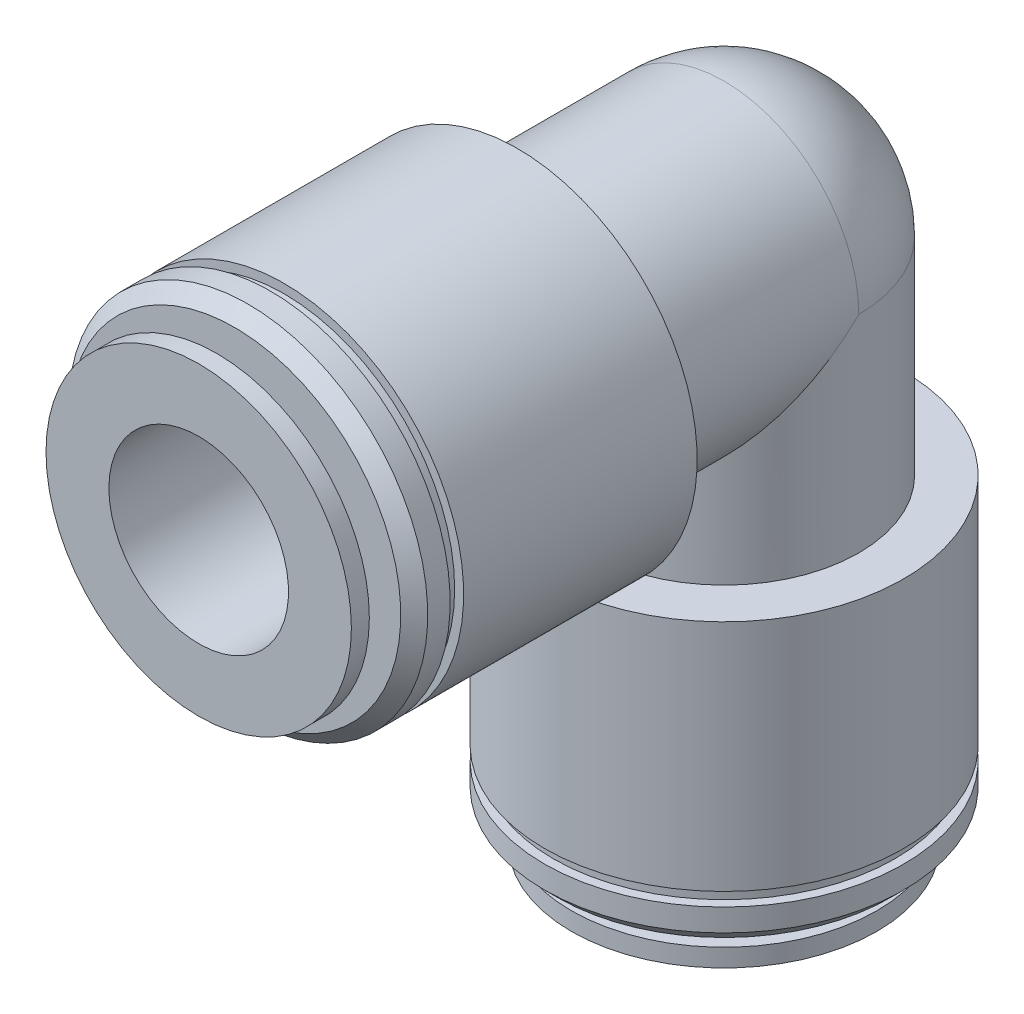
SolidWorks part; units mm, degrees
ref_plane "Спереди" through (0, 0, 0) normal (0, 0, 1) x (1, 0, 0)
ref_plane "Сверху" through (0, 0, 0) normal (0, 1, 0) x (1, 0, 0)
ref_plane "Справа" through (0, 0, 0) normal (1, 0, 0) x (0, 0, -1)
sketch "Эскиз2" plane through (0, 0, 0) normal (0, 0, 1) x (1, 0, 0)
  line L0 (0, 22.5) -> (0, 37.5)
  line L2 (0, 22.5) -> (7.5, 22.5)
  line L3 (7.5, 22.5) -> (7.5, 30)
  arc A0 (7.5, 30) -> (0, 37.5) centre (0, 30) ccw
revolve "Повернуть1" add sketch "Эскиз2" angle 360 about L0
sketch "Эскиз3" plane through (0, 0, 0) normal (0, 0, 1) x (1, 0, 0)
  arc A0 (7.5, 30) -> (-7.5, 30) centre (0, 30) ccw construction
  circle A1 centre (0, 30) radius 7.5
  dimension "D1" = 15
extrude "Бобышка-Вытянуть2" add sketch "Эскиз3" along normal blind 11.5
sketch "Эскиз4" plane through (0, 0, 11.5) normal (0, 0, 1) x (1, 0, 0)
  circle A0 centre (0, 30) radius 10
  dimension "D1" = 20
extrude "Бобышка-Вытянуть3" add sketch "Эскиз4" along normal blind 13
sketch "Эскиз7" plane through (0, 22.5, 0) normal (0, -1, 0) x (1, 0, 0)
  circle A1 centre (0, 0) radius 7.5
  dimension "D1" = 15
extrude "Бобышка-Вытянуть4" add sketch "Эскиз7" along normal blind 4
sketch "Эскиз8" plane through (0, 18.5, 0) normal (0, -1, 0) x (1, 0, 0)
  circle A0 centre (0, 0) radius 10
  dimension "D1" = 20
extrude "Бобышка-Вытянуть6" add sketch "Эскиз8" along normal blind 13 contours A0
sketch "Эскиз9" plane through (0, 0, 0) normal (1, 0, 0) x (0, 0, -1)
  line L15 (8.5, 1.75) -> (6.5, 1.75)
  line L22 (5, 0.75) -> (8.5, 0.75)
  line L24 (8.5, 0.75) -> (8.5, 1.75)
  line L27 (6.5, 2.75) -> (9.25, 2.75)
  line L28 (10, 3.5) -> (10, 4.75)
  line L29 (9.25, 2.75) -> (10, 3.5)
  line L30 (10, 4.75) -> (9.5, 4.75)
  line L31 (9.5, 4.75) -> (9.5, 5.5)
  line L32 (9.5, 5.5) -> (5, 5.5)
  line L33 (6.5, 1.75) -> (6.5, 2.75)
  line L34 (0, 5.5) -> (0, -3.6089) construction
  line L37 (5, 0.75) -> (5, 5.5)
  line L38 (-10, 5.5) -> (10, 5.5) construction
  point P7 (10, 2.75)
  dimension "D1" = 0.75
  dimension "D2" = 0.75
revolve "Повернуть5" add sketch "Эскиз9" angle 360 about L34
sketch "Эскиз14" plane through (0, 0, 0) normal (1, 0, 0) x (0, 0, -1)
  line L0 (-28.25, 21.5) -> (-28.25, 23.5)
  line L1 (-29.25, 25) -> (-29.25, 21.5)
  line L2 (-29.25, 21.5) -> (-28.25, 21.5)
  line L3 (-27.25, 23.5) -> (-27.25, 20.75)
  line L4 (-26.5, 20) -> (-25.25, 20)
  line L5 (-27.25, 20.75) -> (-26.5, 20)
  line L6 (-25.25, 20) -> (-25.25, 20.5)
  line L7 (-25.25, 20.5) -> (-24.5, 20.5)
  line L8 (-24.5, 20.5) -> (-24.5, 25)
  line L9 (-28.25, 23.5) -> (-27.25, 23.5)
  line L10 (-24.5, 30) -> (-33.6089, 30) construction
  line L11 (-29.25, 25) -> (-24.5, 25)
  point P4 (-27.25, 20)
  dimension "D1" = 0.75
  dimension "D2" = 0.75
revolve "Повернуть6" add sketch "Эскиз14" angle 360 about L10
sketch "Эскиз10" plane through (0, 5.5, 0) normal (0, -1, 0) x (1, 0, 0)
  circle A1 centre (0, 0) radius 5
  circle A2 centre (0, 0) radius 5
  dimension "D1" = 0
extrude "Вырез-Вытянуть1" cut sketch "Эскиз10" against normal blind 25
sketch "Эскиз11" plane through (0, 0, 24.5) normal (0, 0, 1) x (1, 0, 0)
  circle A0 centre (0, 30) radius 5 construction
  circle A5 centre (0, 30) radius 5
extrude "Вырез-Вытянуть2" cut sketch "Эскиз11" against normal blind 21
